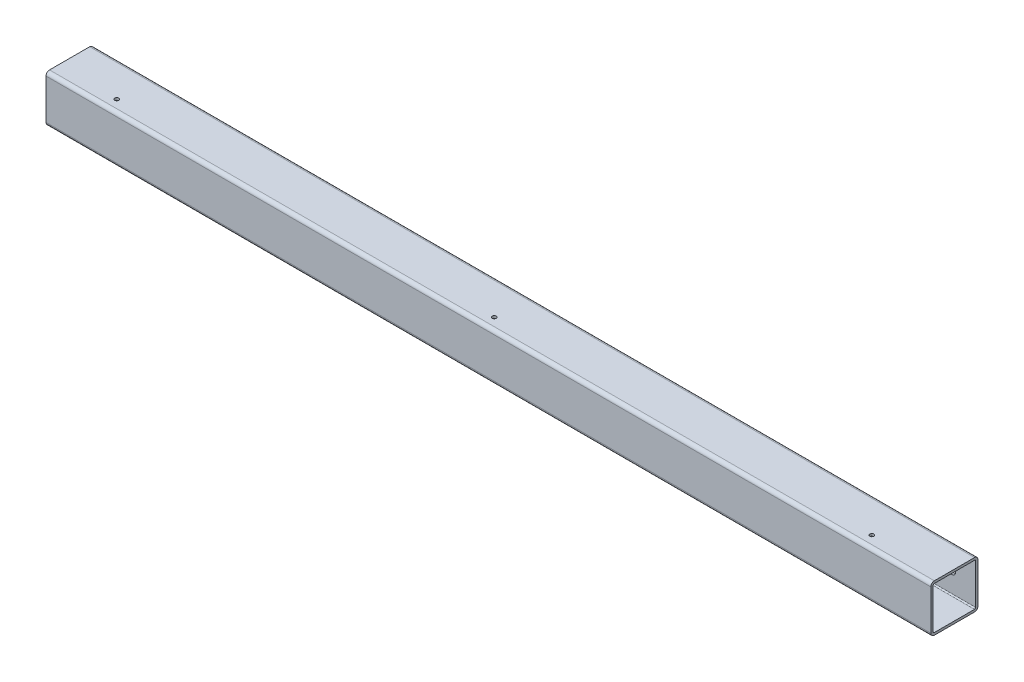
SolidWorks part; units mm, degrees
material "Q235A焊接件"
ref_plane "前视" through (0, 0, 0) normal (0, 0, 1) x (1, 0, 0)
ref_plane "上视" through (0, 0, 0) normal (0, 1, 0) x (1, 0, 0)
ref_plane "右视" through (0, 0, 0) normal (1, 0, 0) x (0, 0, -1)
sketch "草图1" plane through (0, 0, 0) normal (0, 0, 1) x (1, 0, 0)
  line L0 (0, 0) -> (1500, 0)
  dimension "D1" = 1500
other "结构构件1"
ref_plane "基准面1" through (0, 0, 0) normal (1, 0, 0) x (0, 1, 0)
sketch "Sketch11" plane through (0, 0, 0) normal (1, 0, 0) x (0, 1, 0)
  line L0 (-34, -36) -> (34, -36)
  line L1 (-36, -34) -> (-36, 34)
  line L2 (34, 36) -> (-34, 36)
  line L3 (36, 34) -> (36, -34)
  line L4 (-34, -40) -> (34, -40)
  line L5 (-40, -34) -> (-40, 34)
  line L6 (34, 40) -> (-34, 40)
  line L7 (40, 34) -> (40, -34)
  arc A0 (40, 34) -> (34, 40) centre (34, 34) ccw
  arc A1 (34, -40) -> (40, -34) centre (34, -34) ccw
  arc A2 (-40, -34) -> (-34, -40) centre (-34, -34) ccw
  arc A3 (-34, 40) -> (-40, 34) centre (-34, 34) ccw
  arc A4 (-34, 36) -> (-36, 34) centre (-34, 34) ccw
  arc A5 (36, 34) -> (34, 36) centre (34, 34) ccw
  arc A6 (34, -36) -> (36, -34) centre (34, -34) ccw
  arc A7 (-36, -34) -> (-34, -36) centre (-34, -34) ccw
  point P0 (-40, 0)
  point P1 (40, 0)
  point P2 (0, 40)
  point P3 (0, -40)
  point P4 (0, 0)
  point P5 (-40, -40)
  point P6 (40, -40)
  point P7 (40, 40)
  point P8 (-40, 40)
  point P33 (0, 0)
  dimension "D1" = 6
  dimension "Thickness" = 4
  dimension "V_leg" = 80
hole_wizard "M10 间隙孔1" positions "草图5" profile "草图4" hole size "M10" standard "GB"
sketch "草图5" plane through (11.4444, -11.4846, -36) normal (0, 0, 1) x (1, 0, 0)
  line L0 (1488.5556, 45.4846) -> (1488.5556, -22.5154) construction
  line L1 (1488.5556, 51.4846) -> (-11.4444, 51.4846) construction
  point P3 (1368.5556, 11.4846)
  point P5 (1448.5556, 11.4846)
  dimension "D1" = 80
  dimension "D2" = 40
  dimension "D3" = 40
sketch "草图4" plane through (1380, 0, -36) normal (1, 0, 0) x (0, -1, 0)
  line L0 (0, 0) -> (0, 33.6052)
  line L1 (0, 33.6052) -> (6, 30)
  line L2 (6, 30) -> (6, 0)
  line L5 (6, 0) -> (0, 0)
  line L10 (0, 33.6052) -> (-6, 30) construction
  line L11 (0, -6.35) -> (0, 107.95) construction
  dimension "孔直径" = 12
  dimension "孔深度" = 30
  dimension "导头角度" = 118
ref_plane "基准面2" through (750, 0, 0) normal (-1, 0, 0) x (0, 0, 1)
mirror "镜向1" about plane through (750, 0, 0) normal (-1, 0, 0) of "M10 间隙孔1"
hole_wizard "M8 螺纹孔1" [suppressed] positions "草图7" profile "草图6" tap size "M8" standard "GB"
sketch "草图7" plane through (0, 40, 0) normal (0, 1, 0) x (-1, 0, 0)
  line L16 (-110, 20) -> (-90, 20) construction
  line L17 (-800, 20) -> (-780, 20) construction
  line L18 (-1490, 20) -> (-1470, 20) construction
  line L19 (-1690, 20) -> (-1670, 20) construction
  line L20 (-2380, 20) -> (-2360, 20) construction
  line L21 (-3070, 20) -> (-3050, 20) construction
  point P119 (-100, 20)
  point P122 (-790, 20)
  point P125 (-1480, 20)
  point P128 (-1680, 20)
  point P132 (-2370, 20)
  point P135 (-3060, 20)
  dimension "D1" = 20
  dimension "D2" = 20
  dimension "D3" = 20
  dimension "D4" = 20
  dimension "D5" = 20
  dimension "D6" = 20
sketch "草图6" plane through (100, 40, 20) normal (1, 0, 0) x (0, 0, 1)
  line L0 (0, 0) -> (0, 24.2929)
  line L1 (0, 24.2929) -> (3.4, 22.25)
  line L2 (3.4, 22.25) -> (3.4, 0)
  line L5 (3.4, 0) -> (0, 0)
  line L10 (0, 24.2929) -> (-3.4, 22.25) construction
  line L11 (0, -6.35) -> (0, 107.95) construction
  dimension "螺纹孔钻头直径" = 6.8
  dimension "螺纹孔钻头深度" = 22.25
  dimension "导头角度" = 118
cosmetic thread "孔螺蚊线3" [suppressed] parameters "D1"=4, "D2"=8
cosmetic thread "孔螺蚊线4" [suppressed] parameters "D1"=4, "D2"=8
cosmetic thread "孔螺蚊线5" [suppressed] parameters "D1"=4, "D2"=8
cosmetic thread "孔螺蚊线6" [suppressed] parameters "D1"=4, "D2"=8
cosmetic thread "孔螺蚊线7" [suppressed] parameters "D1"=4, "D2"=8
hole_wizard "M8 螺纹孔2" positions "草图9" profile "草图8" tap size "M8" standard "GB"
sketch "草图9" plane through (0, 40, 0) normal (0, 1, 0) x (-1, 0, 0)
  line L4 (-110, 20) -> (-90, 20) construction
  line L7 (-750, 20) -> (-730, 20) construction
  line L10 (-1390, 20) -> (-1370, 20) construction
  line L13 (-1590, 20) -> (-1570, 20) construction
  line L16 (-2230, 20) -> (-2210, 20) construction
  line L19 (-2870, 20) -> (-2850, 20) construction
  point P11 (-100, 20)
  point P49 (-740, 20)
  point P51 (-1380, 20)
  point P53 (-1580, 20)
  point P55 (-2220, 20)
  point P57 (-2860, 20)
  dimension "D1" = 20
sketch "草图8" plane through (100, 40, 20) normal (1, 0, 0) x (0, 0, 1)
  line L0 (0, 0) -> (0, 24.2929)
  line L1 (0, 24.2929) -> (3.4, 22.25)
  line L2 (3.4, 22.25) -> (3.4, 0)
  line L5 (3.4, 0) -> (0, 0)
  line L10 (0, 24.2929) -> (-3.4, 22.25) construction
  line L11 (0, -6.35) -> (0, 107.95) construction
  dimension "螺纹孔钻头直径" = 6.8
  dimension "螺纹孔钻头深度" = 22.25
  dimension "导头角度" = 118
cosmetic thread "孔螺蚊线12" parameters "D1"=4, "D2"=8
cosmetic thread "孔螺蚊线13" parameters "D1"=4, "D2"=8
cosmetic thread "孔螺蚊线15" parameters "D1"=4, "D2"=8
